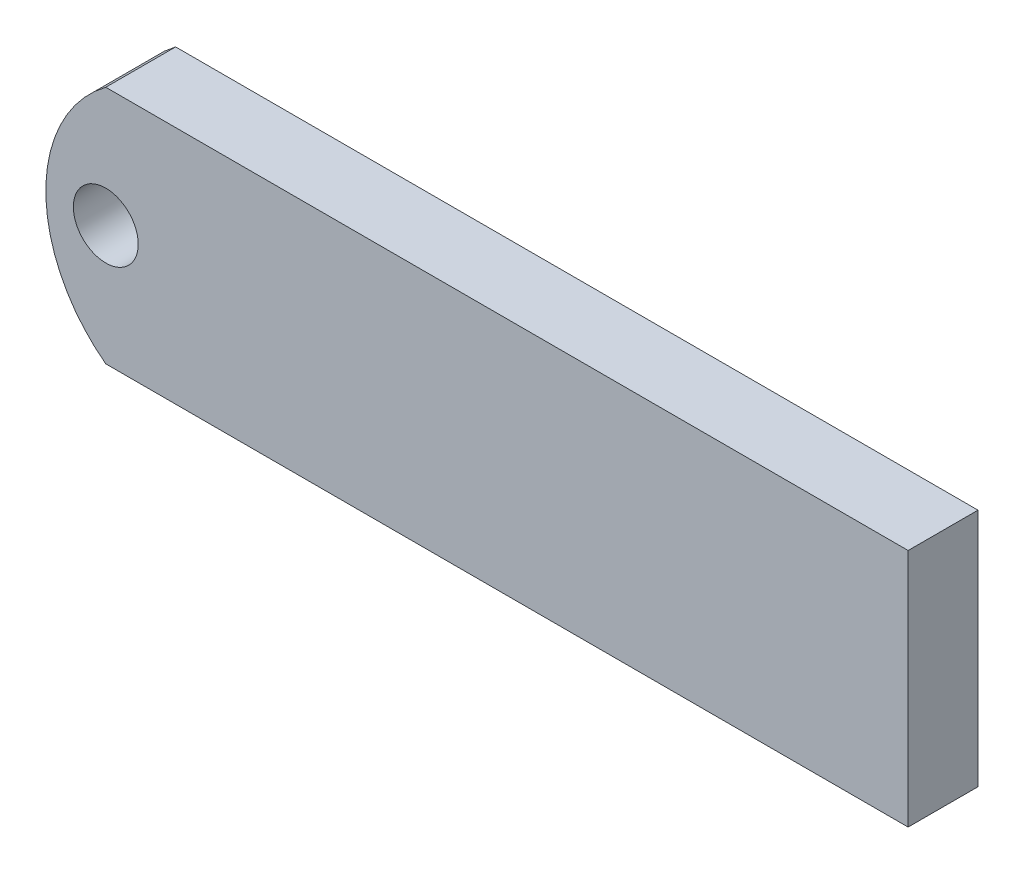
SolidWorks part; units mm, degrees
ref_plane "Alzado" through (0, 0, 0) normal (0, 0, 1) x (1, 0, 0)
ref_plane "Planta" through (0, 0, 0) normal (0, 1, 0) x (1, 0, 0)
ref_plane "Vista lateral" through (0, 0, 0) normal (1, 0, 0) x (0, 0, -1)
sketch "Croquis1" plane through (0, 0, 0) normal (0, 0, 1) x (1, 0, 0)
  line L0 (0, 12) -> (80.3872, 12)
  line L1 (80.3872, 12) -> (80.3872, -12)
  line L2 (80.3872, -12) -> (0, -12)
  line L3 (9, 30.8763) -> (9, 0) construction
  line L4 (9, 0) -> (0, 0) construction
  line L5 (0, 0) -> (-6, 0) construction
  line L6 (0, 0) -> (0, 12) construction
  line L7 (18.8041, 12) -> (18.8041, -12) construction
  line L8 (0, 0) -> (18.8041, 0) construction
  line L9 (0, 12) -> (0, -12) construction
  circle A5 centre (0, 0) radius 3.25
  arc A7 (0, 12) -> (0, -12) centre (8.9849, 0) ccw
  dimension "D2" = 6.5
  dimension "D1" = 24
  dimension "D3" = 9
  dimension "D4" = 6
extrude "Saliente-Extruir1" add sketch "Croquis1" along normal blind 7
